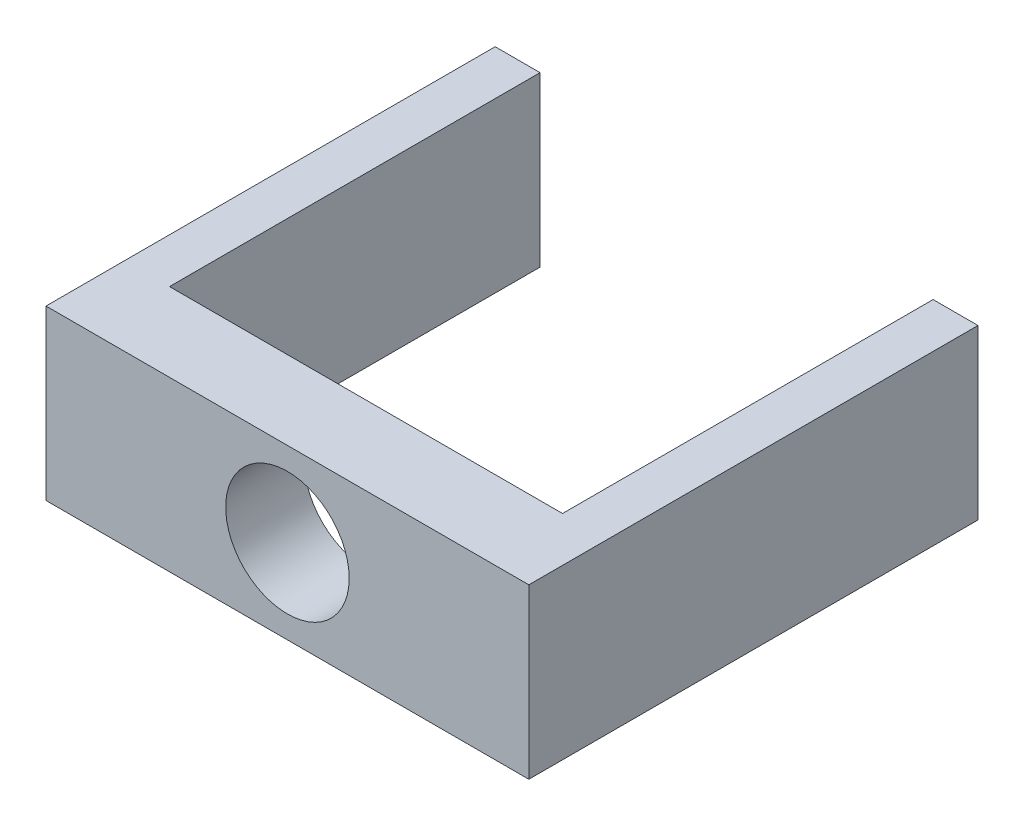
SolidWorks part; units mm, degrees
ref_plane "Ön Düzlem" through (0, 0, 0) normal (0, 0, 1) x (1, 0, 0)
ref_plane "Üst Düzlem" through (0, 0, 0) normal (0, 1, 0) x (1, 0, 0)
ref_plane "Sağ Düzlem" through (0, 0, 0) normal (1, 0, 0) x (0, 0, -1)
sketch "Sketch1" plane through (0, 0, 0) normal (0, 0, 1) x (1, 0, 0)
  line L1 (-17.5, 7.5) -> (17.5, 7.5)
  line L2 (-17.5, 7.5) -> (-17.5, -7.5)
  line L3 (-17.5, -7.5) -> (17.5, -7.5)
  line L4 (17.5, 7.5) -> (17.5, -7.5)
  line L5 (-17.5, 7.5) -> (17.5, -7.5) construction
  line L6 (-17.5, -7.5) -> (17.5, 7.5) construction
  circle A0 centre (0, 0) radius 5.5
  point P0 (0, 0)
  dimension "D3" = 11
  dimension "D1" = 15
  dimension "D2" = 35
extrude "Boss-Extrude1" add sketch "Sketch1" along normal blind 7
sketch "Sketch2" plane through (0, 0, 7) normal (0, 0, 1) x (1, 0, 0)
  line L0 (17.5, -7.5) -> (17.5, 7.5)
  line L1 (17.5, -7.5) -> (21.5, -7.5)
  line L2 (17.5, 7.5) -> (21.5, 7.5)
  line L3 (21.5, -7.5) -> (21.5, 7.5)
  line L4 (-17.5, -7.5) -> (-17.5, 7.5)
  line L5 (-17.5, -7.5) -> (-21.5, -7.5)
  line L6 (-17.5, 7.5) -> (-21.5, 7.5)
  line L7 (-21.5, -7.5) -> (-21.5, 7.5)
  dimension "D1" = 4
  dimension "D2" = 4
extrude "Boss-Extrude2" add sketch "Sketch2" against normal blind 40
